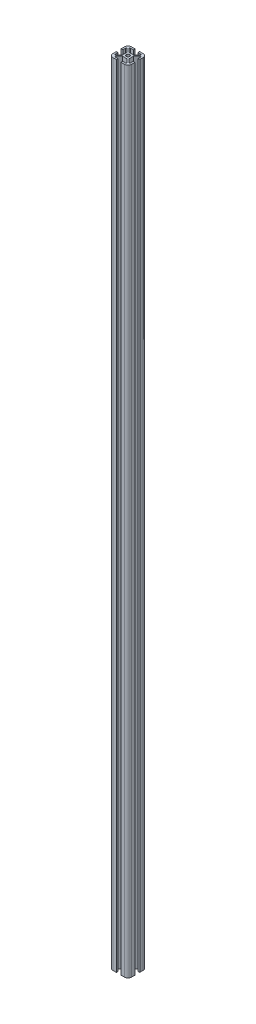
SolidWorks part; units mm, degrees
ref_plane "Front Plane" through (0, 0, 0) normal (0, 0, 1) x (1, 0, 0)
ref_plane "Top Plane" through (0, 0, 0) normal (0, 1, 0) x (1, 0, 0)
ref_plane "Right Plane" through (0, 0, 0) normal (1, 0, 0) x (0, 0, -1)
sketch "Sketch1" plane through (0, 0, 0) normal (0, 1, 0) x (1, 0, 0)
  line L0 (-35, 50) -> (35, 50)
  line L1 (50, 35) -> (50, -35)
  line L2 (35, 50) -> (84.4975, 99.4975)
  line L3 (35, 50) -> (50, 50) construction
  line L4 (50, 35) -> (99.4975, 84.4975)
  line L5 (-141.1793, 88.3883) -> (-141.1793, 37.5)
  line L6 (35, 141.179) -> (88.5607, 141.179)
  line L7 (141.1793, 88.3883) -> (141.1793, 37.5)
  line L8 (141.1793, 37.5) -> (116.1793, 37.5)
  line L9 (35, 141.179) -> (35, 116.179)
  line L10 (116.1793, 37.5) -> (116.1793, 77.5877)
  line L11 (35, 116.179) -> (77.5878, 116.179)
  line L12 (0, 244.4415) -> (0, -207.0612) construction
  line L13 (216.8097, 0) -> (-231.8125, 0) construction
  line L14 (-141.1793, 37.5) -> (-116.1793, 37.5)
  line L15 (-116.1793, 37.5) -> (-116.1793, 77.5877)
  line L16 (-50, 35) -> (-99.4975, 84.4975)
  line L17 (-50, 35) -> (-50, -35)
  line L18 (-35, 50) -> (-84.4975, 99.4975)
  line L19 (-35, 116.179) -> (-77.5878, 116.179)
  line L20 (-35, 141.179) -> (-35, 116.179)
  line L21 (-35, 141.179) -> (-88.5607, 141.179)
  line L22 (50, -35) -> (99.4975, -84.4975)
  line L23 (116.1793, -37.5) -> (116.1793, -77.5877)
  line L24 (141.1793, -37.5) -> (116.1793, -37.5)
  line L25 (141.1793, -88.3883) -> (141.1793, -37.5)
  line L26 (35, -141.179) -> (88.5607, -141.179)
  line L27 (35, -141.179) -> (35, -116.179)
  line L28 (35, -116.179) -> (77.5878, -116.179)
  line L29 (35, -50) -> (84.4975, -99.4975)
  line L30 (-35, -50) -> (35, -50)
  line L31 (-35, -50) -> (-84.4975, -99.4975)
  line L32 (-35, -116.179) -> (-77.5878, -116.179)
  line L33 (-35, -141.179) -> (-35, -116.179)
  line L34 (-35, -141.179) -> (-88.5607, -141.179)
  line L35 (-141.1793, -88.3883) -> (-141.1793, -37.5)
  line L36 (-141.1793, -37.5) -> (-116.1793, -37.5)
  line L37 (-116.1793, -37.5) -> (-116.1793, -77.5877)
  line L38 (-50, -35) -> (-99.4975, -84.4975)
  circle A1 centre (0, 0) radius 25
  arc A2 (88.5607, 141.179) -> (141.1793, 88.3883) centre (88.3883, 88.3883) cw
  arc A3 (77.5878, 116.179) -> (84.4975, 99.4975) centre (77.5878, 106.4072) cw
  arc A4 (116.1793, 77.5877) -> (99.4975, 84.4975) centre (106.4073, 77.5877) ccw
  arc A5 (-88.5607, 141.179) -> (-141.1793, 88.3883) centre (-88.3883, 88.3883) ccw
  arc A6 (-116.1793, 77.5877) -> (-99.4975, 84.4975) centre (-106.4073, 77.5877) cw
  arc A7 (-77.5878, 116.179) -> (-84.4975, 99.4975) centre (-77.5878, 106.4072) ccw
  arc A8 (116.1793, -77.5877) -> (99.4975, -84.4975) centre (106.4073, -77.5877) cw
  arc A9 (88.5607, -141.179) -> (141.1793, -88.3883) centre (88.3883, -88.3883) ccw
  arc A10 (77.5878, -116.179) -> (84.4975, -99.4975) centre (77.5878, -106.4072) ccw
  arc A11 (-77.5878, -116.179) -> (-84.4975, -99.4975) centre (-77.5878, -106.4072) cw
  arc A12 (-88.5607, -141.179) -> (-141.1793, -88.3883) centre (-88.3883, -88.3883) cw
  arc A13 (-116.1793, -77.5877) -> (-99.4975, -84.4975) centre (-106.4073, -77.5877) ccw
  point P4 (0, 50)
  point P5 (50, 0)
  point P7 (0, 25)
  point P8 (25, 0)
  point P9 (0, 0)
  point P10 (35, 50)
  point P11 (50, 35)
  point P21 (0, 25)
  point P22 (0, 0)
  point P37 (0, 0)
  point P45 (0, 0)
  point P46 (50, 0)
  point P47 (0, 50)
  point P81 (-50, 0)
  point P82 (0, 0)
  point P83 (0, 0)
  point P84 (0, 0)
  point P85 (-35, 50)
  dimension "D2" = 282.358
  dimension "D3" = 45
  dimension "D4" = 70
  dimension "D5" = 35
  dimension "D6" = 35
  dimension "D9" = 25
  dimension "D10" = 25
extrude "Boss-Extrude1" add sketch "Sketch1" along normal blind 12000
